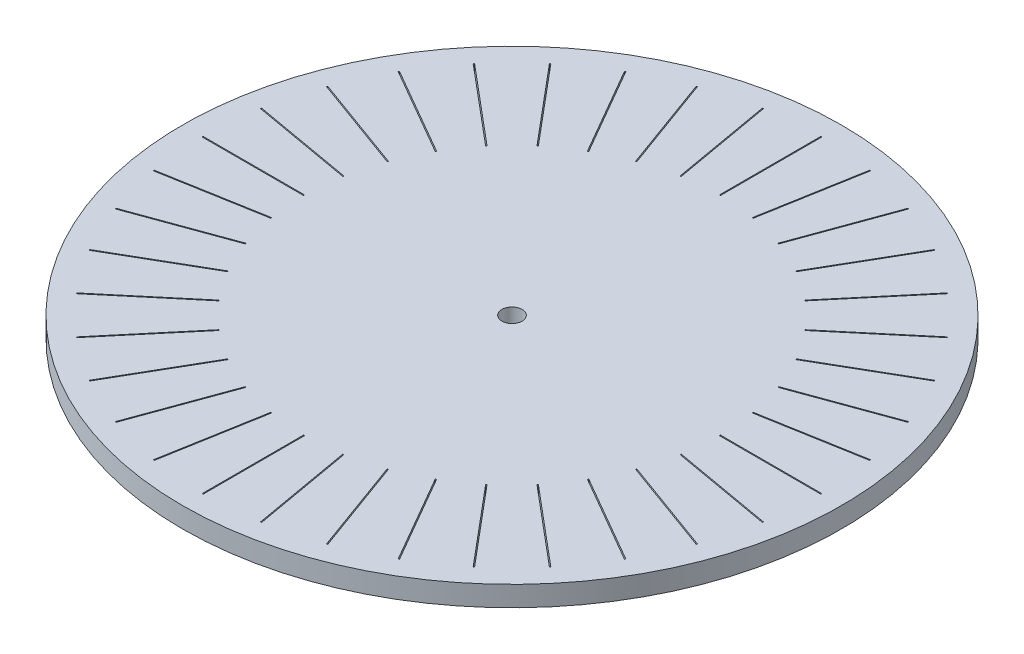
SolidWorks part; units mm, degrees
ref_plane "Front Plane" through (0, 0, 0) normal (0, 0, 1) x (1, 0, 0)
ref_plane "Top Plane" through (0, 0, 0) normal (0, 1, 0) x (1, 0, 0)
ref_plane "Right Plane" through (0, 0, 0) normal (1, 0, 0) x (0, 0, -1)
sketch "Sketch1" plane through (0, 0, 0) normal (0, 1, 0) x (1, 0, 0)
  line L0 (0, 82.55) -> (0, -82.55) construction
  line L1 (-82.55, 0) -> (82.55, 0) construction
  line L2 (13.3275, 76.3151) -> (13.5776, 76.271)
  line L3 (-0.127, 77.47) -> (0.127, 77.47)
  line L4 (-0.127, 77.47) -> (-0.127, 52.07)
  line L5 (-0.127, 52.07) -> (0.127, 52.07)
  line L6 (0.127, 77.47) -> (0.127, 52.07)
  line L7 (-0.127, 77.47) -> (0.127, 52.07) construction
  line L8 (-0.127, 52.07) -> (0.127, 77.47) construction
  line L9 (13.3275, 76.3151) -> (8.9168, 51.301)
  line L10 (8.9168, 51.301) -> (9.1669, 51.2569)
  line L11 (13.5776, 76.271) -> (9.1669, 51.2569)
  line L12 (13.3275, 76.3151) -> (9.1669, 51.2569) construction
  line L13 (8.9168, 51.301) -> (13.5776, 76.271) construction
  line L14 (26.377, 72.8414) -> (26.6156, 72.7546)
  line L15 (26.377, 72.8414) -> (17.6896, 48.9732)
  line L16 (17.6896, 48.9732) -> (17.9283, 48.8864)
  line L17 (26.6156, 72.7546) -> (17.9283, 48.8864)
  line L18 (26.377, 72.8414) -> (17.9283, 48.8864) construction
  line L19 (17.6896, 48.9732) -> (26.6156, 72.7546) construction
  line L20 (38.625, 67.1545) -> (38.845, 67.0275)
  line L21 (38.625, 67.1545) -> (25.925, 45.1574)
  line L22 (25.925, 45.1574) -> (26.145, 45.0304)
  line L23 (38.845, 67.0275) -> (26.145, 45.0304)
  line L24 (38.625, 67.1545) -> (26.145, 45.0304) construction
  line L25 (25.925, 45.1574) -> (38.845, 67.0275) construction
  line L26 (49.6995, 59.4271) -> (49.894, 59.2638)
  line L27 (49.6995, 59.4271) -> (33.3727, 39.9696)
  line L28 (33.3727, 39.9696) -> (33.5672, 39.8063)
  line L29 (49.894, 59.2638) -> (33.5672, 39.8063)
  line L30 (49.6995, 59.4271) -> (33.5672, 39.8063) construction
  line L31 (33.3727, 39.9696) -> (49.894, 59.2638) construction
  line L32 (59.2638, 49.894) -> (59.4271, 49.6995)
  line L33 (59.2638, 49.894) -> (39.8063, 33.5672)
  line L34 (39.8063, 33.5672) -> (39.9696, 33.3727)
  line L35 (59.4271, 49.6995) -> (39.9696, 33.3727)
  line L36 (59.2638, 49.894) -> (39.9696, 33.3727) construction
  line L37 (39.8063, 33.5672) -> (59.4271, 49.6995) construction
  line L38 (67.0275, 38.845) -> (67.1545, 38.625)
  line L39 (67.0275, 38.845) -> (45.0304, 26.145)
  line L40 (45.0304, 26.145) -> (45.1574, 25.925)
  line L41 (67.1545, 38.625) -> (45.1574, 25.925)
  line L42 (67.0275, 38.845) -> (45.1574, 25.925) construction
  line L43 (45.0304, 26.145) -> (67.1545, 38.625) construction
  line L44 (72.7546, 26.6156) -> (72.8414, 26.377)
  line L45 (72.7546, 26.6156) -> (48.8864, 17.9283)
  line L46 (48.8864, 17.9283) -> (48.9732, 17.6896)
  line L47 (72.8414, 26.377) -> (48.9732, 17.6896)
  line L48 (72.7546, 26.6156) -> (48.9732, 17.6896) construction
  line L49 (48.8864, 17.9283) -> (72.8414, 26.377) construction
  line L50 (76.271, 13.5776) -> (76.3151, 13.3275)
  line L51 (76.271, 13.5776) -> (51.2569, 9.1669)
  line L52 (51.2569, 9.1669) -> (51.301, 8.9168)
  line L53 (76.3151, 13.3275) -> (51.301, 8.9168)
  line L54 (76.271, 13.5776) -> (51.301, 8.9168) construction
  line L55 (51.2569, 9.1669) -> (76.3151, 13.3275) construction
  line L56 (77.47, 0.127) -> (77.47, -0.127)
  line L57 (77.47, 0.127) -> (52.07, 0.127)
  line L58 (52.07, 0.127) -> (52.07, -0.127)
  line L59 (77.47, -0.127) -> (52.07, -0.127)
  line L60 (77.47, 0.127) -> (52.07, -0.127) construction
  line L61 (52.07, 0.127) -> (77.47, -0.127) construction
  line L62 (76.3151, -13.3275) -> (76.271, -13.5776)
  line L63 (76.3151, -13.3275) -> (51.301, -8.9168)
  line L64 (51.301, -8.9168) -> (51.2569, -9.1669)
  line L65 (76.271, -13.5776) -> (51.2569, -9.1669)
  line L66 (76.3151, -13.3275) -> (51.2569, -9.1669) construction
  line L67 (51.301, -8.9168) -> (76.271, -13.5776) construction
  line L68 (72.8414, -26.377) -> (72.7546, -26.6156)
  line L69 (72.8414, -26.377) -> (48.9732, -17.6896)
  line L70 (48.9732, -17.6896) -> (48.8864, -17.9283)
  line L71 (72.7546, -26.6156) -> (48.8864, -17.9283)
  line L72 (72.8414, -26.377) -> (48.8864, -17.9283) construction
  line L73 (48.9732, -17.6896) -> (72.7546, -26.6156) construction
  line L74 (67.1545, -38.625) -> (67.0275, -38.845)
  line L75 (67.1545, -38.625) -> (45.1574, -25.925)
  line L76 (45.1574, -25.925) -> (45.0304, -26.145)
  line L77 (67.0275, -38.845) -> (45.0304, -26.145)
  line L78 (67.1545, -38.625) -> (45.0304, -26.145) construction
  line L79 (45.1574, -25.925) -> (67.0275, -38.845) construction
  line L80 (59.4271, -49.6995) -> (59.2638, -49.894)
  line L81 (59.4271, -49.6995) -> (39.9696, -33.3727)
  line L82 (39.9696, -33.3727) -> (39.8063, -33.5672)
  line L83 (59.2638, -49.894) -> (39.8063, -33.5672)
  line L84 (59.4271, -49.6995) -> (39.8063, -33.5672) construction
  line L85 (39.9696, -33.3727) -> (59.2638, -49.894) construction
  line L86 (49.894, -59.2638) -> (49.6995, -59.4271)
  line L87 (49.894, -59.2638) -> (33.5672, -39.8063)
  line L88 (33.5672, -39.8063) -> (33.3727, -39.9696)
  line L89 (49.6995, -59.4271) -> (33.3727, -39.9696)
  line L90 (49.894, -59.2638) -> (33.3727, -39.9696) construction
  line L91 (33.5672, -39.8063) -> (49.6995, -59.4271) construction
  line L92 (38.845, -67.0275) -> (38.625, -67.1545)
  line L93 (38.845, -67.0275) -> (26.145, -45.0304)
  line L94 (26.145, -45.0304) -> (25.925, -45.1574)
  line L95 (38.625, -67.1545) -> (25.925, -45.1574)
  line L96 (38.845, -67.0275) -> (25.925, -45.1574) construction
  line L97 (26.145, -45.0304) -> (38.625, -67.1545) construction
  line L98 (26.6156, -72.7546) -> (26.377, -72.8414)
  line L99 (26.6156, -72.7546) -> (17.9283, -48.8864)
  line L100 (17.9283, -48.8864) -> (17.6896, -48.9732)
  line L101 (26.377, -72.8414) -> (17.6896, -48.9732)
  line L102 (26.6156, -72.7546) -> (17.6896, -48.9732) construction
  line L103 (17.9283, -48.8864) -> (26.377, -72.8414) construction
  line L104 (13.5776, -76.271) -> (13.3275, -76.3151)
  line L105 (13.5776, -76.271) -> (9.1669, -51.2569)
  line L106 (9.1669, -51.2569) -> (8.9168, -51.301)
  line L107 (13.3275, -76.3151) -> (8.9168, -51.301)
  line L108 (13.5776, -76.271) -> (8.9168, -51.301) construction
  line L109 (9.1669, -51.2569) -> (13.3275, -76.3151) construction
  line L110 (0.127, -77.47) -> (-0.127, -77.47)
  line L111 (0.127, -77.47) -> (0.127, -52.07)
  line L112 (0.127, -52.07) -> (-0.127, -52.07)
  line L113 (-0.127, -77.47) -> (-0.127, -52.07)
  line L114 (0.127, -77.47) -> (-0.127, -52.07) construction
  line L115 (0.127, -52.07) -> (-0.127, -77.47) construction
  line L116 (-13.3275, -76.3151) -> (-13.5776, -76.271)
  line L117 (-13.3275, -76.3151) -> (-8.9168, -51.301)
  line L118 (-8.9168, -51.301) -> (-9.1669, -51.2569)
  line L119 (-13.5776, -76.271) -> (-9.1669, -51.2569)
  line L120 (-13.3275, -76.3151) -> (-9.1669, -51.2569) construction
  line L121 (-8.9168, -51.301) -> (-13.5776, -76.271) construction
  line L122 (-26.377, -72.8414) -> (-26.6156, -72.7546)
  line L123 (-26.377, -72.8414) -> (-17.6896, -48.9732)
  line L124 (-17.6896, -48.9732) -> (-17.9283, -48.8864)
  line L125 (-26.6156, -72.7546) -> (-17.9283, -48.8864)
  line L126 (-26.377, -72.8414) -> (-17.9283, -48.8864) construction
  line L127 (-17.6896, -48.9732) -> (-26.6156, -72.7546) construction
  line L128 (-38.625, -67.1545) -> (-38.845, -67.0275)
  line L129 (-38.625, -67.1545) -> (-25.925, -45.1574)
  line L130 (-25.925, -45.1574) -> (-26.145, -45.0304)
  line L131 (-38.845, -67.0275) -> (-26.145, -45.0304)
  line L132 (-38.625, -67.1545) -> (-26.145, -45.0304) construction
  line L133 (-25.925, -45.1574) -> (-38.845, -67.0275) construction
  line L134 (-49.6995, -59.4271) -> (-49.894, -59.2638)
  line L135 (-49.6995, -59.4271) -> (-33.3727, -39.9696)
  line L136 (-33.3727, -39.9696) -> (-33.5672, -39.8063)
  line L137 (-49.894, -59.2638) -> (-33.5672, -39.8063)
  line L138 (-49.6995, -59.4271) -> (-33.5672, -39.8063) construction
  line L139 (-33.3727, -39.9696) -> (-49.894, -59.2638) construction
  line L140 (-59.2638, -49.894) -> (-59.4271, -49.6995)
  line L141 (-59.2638, -49.894) -> (-39.8063, -33.5672)
  line L142 (-39.8063, -33.5672) -> (-39.9696, -33.3727)
  line L143 (-59.4271, -49.6995) -> (-39.9696, -33.3727)
  line L144 (-59.2638, -49.894) -> (-39.9696, -33.3727) construction
  line L145 (-39.8063, -33.5672) -> (-59.4271, -49.6995) construction
  line L146 (-67.0275, -38.845) -> (-67.1545, -38.625)
  line L147 (-67.0275, -38.845) -> (-45.0304, -26.145)
  line L148 (-45.0304, -26.145) -> (-45.1574, -25.925)
  line L149 (-67.1545, -38.625) -> (-45.1574, -25.925)
  line L150 (-67.0275, -38.845) -> (-45.1574, -25.925) construction
  line L151 (-45.0304, -26.145) -> (-67.1545, -38.625) construction
  line L152 (-72.7546, -26.6156) -> (-72.8414, -26.377)
  line L153 (-72.7546, -26.6156) -> (-48.8864, -17.9283)
  line L154 (-48.8864, -17.9283) -> (-48.9732, -17.6896)
  line L155 (-72.8414, -26.377) -> (-48.9732, -17.6896)
  line L156 (-72.7546, -26.6156) -> (-48.9732, -17.6896) construction
  line L157 (-48.8864, -17.9283) -> (-72.8414, -26.377) construction
  line L158 (-76.271, -13.5776) -> (-76.3151, -13.3275)
  line L159 (-76.271, -13.5776) -> (-51.2569, -9.1669)
  line L160 (-51.2569, -9.1669) -> (-51.301, -8.9168)
  line L161 (-76.3151, -13.3275) -> (-51.301, -8.9168)
  line L162 (-76.271, -13.5776) -> (-51.301, -8.9168) construction
  line L163 (-51.2569, -9.1669) -> (-76.3151, -13.3275) construction
  line L164 (-77.47, -0.127) -> (-77.47, 0.127)
  line L165 (-77.47, -0.127) -> (-52.07, -0.127)
  line L166 (-52.07, -0.127) -> (-52.07, 0.127)
  line L167 (-77.47, 0.127) -> (-52.07, 0.127)
  line L168 (-77.47, -0.127) -> (-52.07, 0.127) construction
  line L169 (-52.07, -0.127) -> (-77.47, 0.127) construction
  line L170 (-76.3151, 13.3275) -> (-76.271, 13.5776)
  line L171 (-76.3151, 13.3275) -> (-51.301, 8.9168)
  line L172 (-51.301, 8.9168) -> (-51.2569, 9.1669)
  line L173 (-76.271, 13.5776) -> (-51.2569, 9.1669)
  line L174 (-76.3151, 13.3275) -> (-51.2569, 9.1669) construction
  line L175 (-51.301, 8.9168) -> (-76.271, 13.5776) construction
  line L176 (-72.8414, 26.377) -> (-72.7546, 26.6156)
  line L177 (-72.8414, 26.377) -> (-48.9732, 17.6896)
  line L178 (-48.9732, 17.6896) -> (-48.8864, 17.9283)
  line L179 (-72.7546, 26.6156) -> (-48.8864, 17.9283)
  line L180 (-72.8414, 26.377) -> (-48.8864, 17.9283) construction
  line L181 (-48.9732, 17.6896) -> (-72.7546, 26.6156) construction
  line L182 (-67.1545, 38.625) -> (-67.0275, 38.845)
  line L183 (-67.1545, 38.625) -> (-45.1574, 25.925)
  line L184 (-45.1574, 25.925) -> (-45.0304, 26.145)
  line L185 (-67.0275, 38.845) -> (-45.0304, 26.145)
  line L186 (-67.1545, 38.625) -> (-45.0304, 26.145) construction
  line L187 (-45.1574, 25.925) -> (-67.0275, 38.845) construction
  line L188 (-59.4271, 49.6995) -> (-59.2638, 49.894)
  line L189 (-59.4271, 49.6995) -> (-39.9696, 33.3727)
  line L190 (-39.9696, 33.3727) -> (-39.8063, 33.5672)
  line L191 (-59.2638, 49.894) -> (-39.8063, 33.5672)
  line L192 (-59.4271, 49.6995) -> (-39.8063, 33.5672) construction
  line L193 (-39.9696, 33.3727) -> (-59.2638, 49.894) construction
  line L194 (-49.894, 59.2638) -> (-49.6995, 59.4271)
  line L195 (-49.894, 59.2638) -> (-33.5672, 39.8063)
  line L196 (-33.5672, 39.8063) -> (-33.3727, 39.9696)
  line L197 (-49.6995, 59.4271) -> (-33.3727, 39.9696)
  line L198 (-49.894, 59.2638) -> (-33.3727, 39.9696) construction
  line L199 (-33.5672, 39.8063) -> (-49.6995, 59.4271) construction
  line L200 (-38.845, 67.0275) -> (-38.625, 67.1545)
  line L201 (-38.845, 67.0275) -> (-26.145, 45.0304)
  line L202 (-26.145, 45.0304) -> (-25.925, 45.1574)
  line L203 (-38.625, 67.1545) -> (-25.925, 45.1574)
  line L204 (-38.845, 67.0275) -> (-25.925, 45.1574) construction
  line L205 (-26.145, 45.0304) -> (-38.625, 67.1545) construction
  line L206 (-26.6156, 72.7546) -> (-26.377, 72.8414)
  line L207 (-26.6156, 72.7546) -> (-17.9283, 48.8864)
  line L208 (-17.9283, 48.8864) -> (-17.6896, 48.9732)
  line L209 (-26.377, 72.8414) -> (-17.6896, 48.9732)
  line L210 (-26.6156, 72.7546) -> (-17.6896, 48.9732) construction
  line L211 (-17.9283, 48.8864) -> (-26.377, 72.8414) construction
  line L212 (-13.5776, 76.271) -> (-13.3275, 76.3151)
  line L213 (-13.5776, 76.271) -> (-9.1669, 51.2569)
  line L214 (-9.1669, 51.2569) -> (-8.9168, 51.301)
  line L215 (-13.3275, 76.3151) -> (-8.9168, 51.301)
  line L216 (-13.5776, 76.271) -> (-8.9168, 51.301) construction
  line L217 (-9.1669, 51.2569) -> (-13.3275, 76.3151) construction
  circle A0 centre (0, 0) radius 82.55
  circle A1 centre (0, 0) radius 2.54
  point P7 (0, 64.77)
  point P13 (41.6334, 49.6167)
  point P15 (11.2472, 63.786)
  point P20 (22.1526, 60.8639)
  point P25 (32.385, 56.0925)
  point P30 (0, 0)
  point P34 (49.6167, 41.6334)
  point P39 (56.0925, 32.385)
  point P44 (60.8639, 22.1526)
  point P49 (63.786, 11.2472)
  point P54 (64.77, 0)
  point P59 (63.786, -11.2472)
  point P64 (60.8639, -22.1526)
  point P69 (56.0925, -32.385)
  point P74 (49.6167, -41.6334)
  point P79 (41.6334, -49.6167)
  point P84 (32.385, -56.0925)
  point P89 (22.1526, -60.8639)
  point P94 (11.2472, -63.786)
  point P99 (0, -64.77)
  point P104 (-11.2472, -63.786)
  point P109 (-22.1526, -60.8639)
  point P114 (-32.385, -56.0925)
  point P119 (-41.6334, -49.6167)
  point P124 (-49.6167, -41.6334)
  point P129 (-56.0925, -32.385)
  point P134 (-60.8639, -22.1526)
  point P139 (-63.786, -11.2472)
  point P144 (-64.77, 0)
  point P149 (-63.786, 11.2472)
  point P154 (-60.8639, 22.1526)
  point P159 (-56.0925, 32.385)
  point P164 (-49.6167, 41.6334)
  point P169 (-41.6334, 49.6167)
  point P174 (-32.385, 56.0925)
  point P179 (-22.1526, 60.8639)
  point P184 (-11.2472, 63.786)
  dimension "D1" = 165.1
  dimension "D6" = 5.08
  dimension "D2" = 5.08
  dimension "D3" = 25.4
  dimension "D4" = 0.254
  dimension "D5" = 36
extrude "Boss-Extrude1" add sketch "Sketch1" along normal blind 5.08
